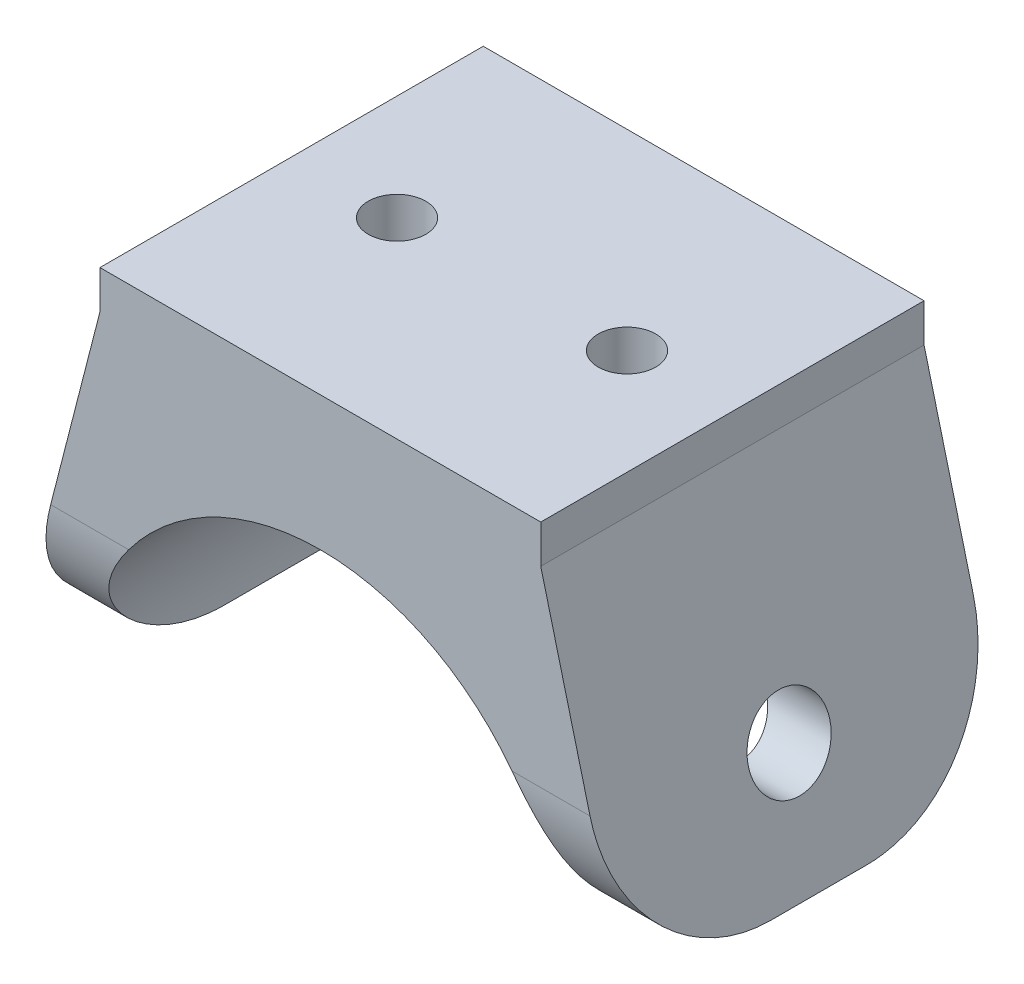
SolidWorks part; units mm, degrees
material "Mahogany"
ref_plane "Front" through (0, 0, 0) normal (0, 0, 1) x (1, 0, 0)
ref_plane "Top" through (0, 0, 0) normal (0, 1, 0) x (1, 0, 0)
ref_plane "Right" through (0, 0, 0) normal (1, 0, 0) x (0, 0, -1)
sketch "Sketch1" plane through (0, 0, 0) normal (0, 0, 1) x (1, 0, 0)
  line L1 (-32, -12) -> (32, -12)
  line L2 (-32, -12) -> (-32, 27)
  line L3 (-32, 27) -> (32, 27)
  line L4 (32, -12) -> (32, 27)
  point P4 (0, -12)
  dimension "D1" = 64
  dimension "D2" = 39
  dimension "D3" = 27
extrude "Boss-Extrude1" add sketch "Sketch1" along normal mid plane 40
sketch "Sketch2" plane through (0, 0, 20) normal (0, 0, 1) x (1, 0, 0)
  line L0 (-32, -12) -> (32, -12) construction
  line L1 (-25, -12) -> (25, -12)
  arc A0 (-25, -12) -> (25, -12) centre (0, -12) cw
  dimension "D1" = 25
extrude "Cut-Extrude1" cut sketch "Sketch2" against normal through all
sketch "Sketch3" plane through (0, 0, 20) normal (0, 0, 1) x (1, 0, 0)
  line L0 (32, -12) -> (23, 23)
  line L1 (23, 23) -> (23, 27)
  line L2 (32, 27) -> (-32, 27) construction
  line L3 (23, 27) -> (32, 27)
  line L4 (32, 27) -> (32, -12)
  point P3 (23, 25)
  dimension "D1" = 23
  dimension "D2" = 4
extrude "Cut-Extrude2" cut sketch "Sketch3" against normal through all
fillet "Fillet1" radius 15 2 edges at (28.5, -12, -20) (28.5, -12, 20)
sketch "Sketch4" plane through (0, 27, 0) normal (0, 1, 0) x (1, 0, 0)
  circle A0 centre (12, 0) radius 3
  dimension "D1" = 6
  dimension "D2" = 12
extrude "Cut-Extrude3" cut sketch "Sketch4" against normal blind 14
mirror "Mirror1" about plane through (0, 0, 0) normal (1, 0, 0) of "Cut-Extrude3", "Fillet1", "Cut-Extrude2"
sketch "Sketch5" plane through (0, 0, 0) normal (1, 0, 0) x (0, 0, -1)
  circle A0 centre (0, 0) radius 4.25
  dimension "D1" = 8.5
extrude "Cut-Extrude4" cut sketch "Sketch5" against normal through all both and the other way through all
